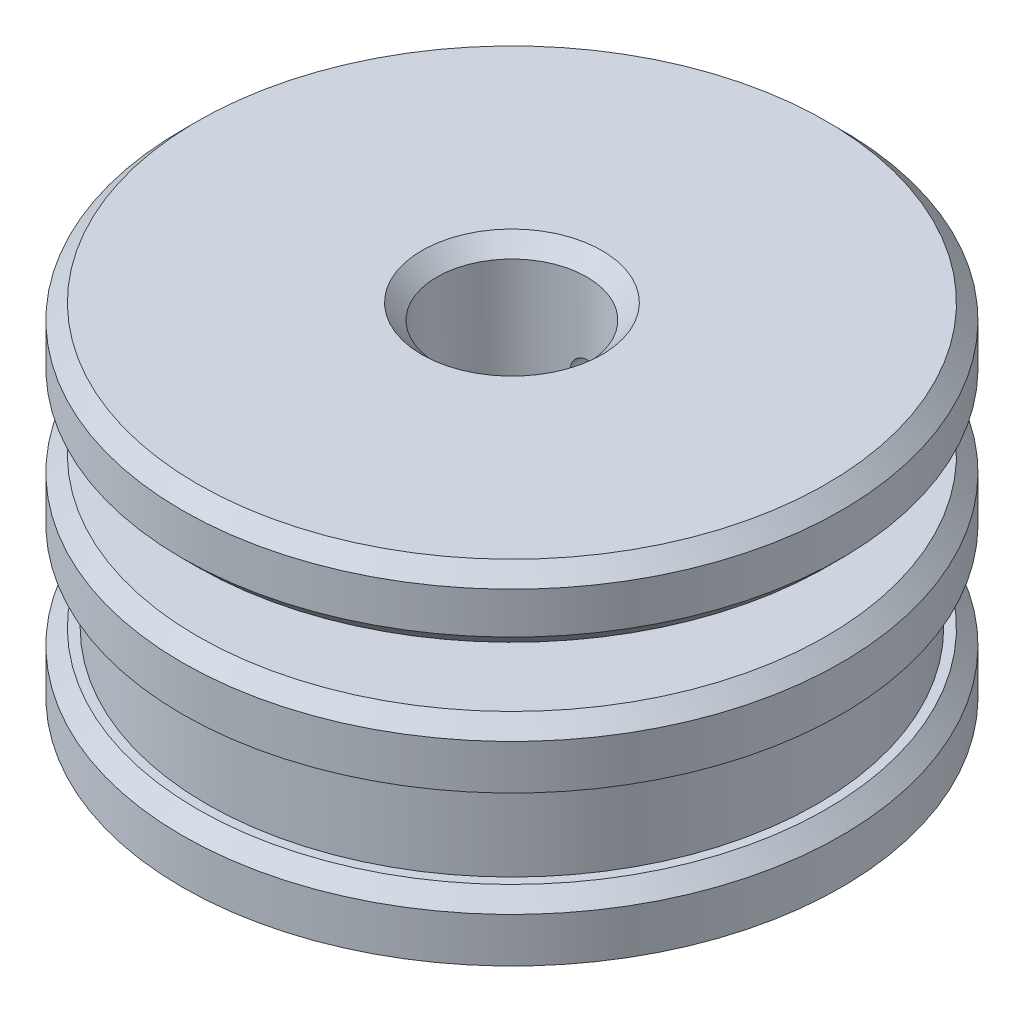
SolidWorks part; units mm, degrees
ref_plane "Front Plane" through (0, 0, 0) normal (0, 0, 1) x (1, 0, 0)
ref_plane "Top Plane" through (0, 0, 0) normal (0, 1, 0) x (1, 0, 0)
ref_plane "Right Plane" through (0, 0, 0) normal (1, 0, 0) x (0, 0, -1)
sketch "Sketch1" plane through (0, 0, 0) normal (0, 1, 0) x (1, 0, 0)
  circle A0 centre (0, 0) radius 2.3813
  circle A1 centre (0, 0) radius 11
  dimension "D1" = 4.7625
  dimension "D2" = 22
extrude "Boss-Extrude1" add sketch "Sketch1" along normal blind 2
sketch "Sketch2" plane through (0, 2, 0) normal (0, 1, 0) x (1, 0, 0)
  circle A0 centre (0, 0) radius 1.1375
  circle A1 centre (0, 0) radius 10.19
  dimension "D1" = 2.275
  dimension "D2" = 20.38
extrude "Boss-Extrude2" add sketch "Sketch2" along normal blind 1.5
sketch "Sketch3" plane through (0, 3.5, 0) normal (0, 1, 0) x (1, 0, 0)
  circle A0 centre (0, 0) radius 10.19
  circle A1 centre (0, 0) radius 2.5
  circle A2 centre (0, 0) radius 10.19 construction
  dimension "D1" = 5
extrude "Boss-Extrude3" add sketch "Sketch3" along normal blind 1.5
sketch "Sketch5" plane through (0, 5, 0) normal (0, 1, 0) x (1, 0, 0)
  circle A0 centre (0, 0) radius 2.5
  circle A1 centre (0, 0) radius 11
  circle A2 centre (0, 0) radius 11 construction
  circle A3 centre (0, 0) radius 2.5 construction
extrude "Boss-Extrude4" add sketch "Sketch5" along normal blind 2
sketch "Sketch6" plane through (0, 7, 0) normal (0, 1, 0) x (1, 0, 0)
  circle A0 centre (0, 0) radius 2.5
  circle A1 centre (0, 0) radius 6.4
  circle A2 centre (0, 0) radius 2.5 construction
  dimension "D1" = 12.8
extrude "Boss-Extrude5" add sketch "Sketch6" along normal blind 2
sketch "Sketch7" plane through (0, 9, 0) normal (0, 1, 0) x (1, 0, 0)
  circle A0 centre (0, 0) radius 2.5
  circle A1 centre (0, 0) radius 11
  circle A2 centre (0, 0) radius 11 construction
  circle A3 centre (0, 0) radius 2.5 construction
extrude "Boss-Extrude6" add sketch "Sketch7" along normal blind 2.4
sketch "Sketch8" plane through (0, 0, 0) normal (0, 0, 1) x (1, 0, 0)
  line L0 (0, 0) -> (0, 2) construction
  line L1 (0, 2) -> (0, 5) construction
  line L2 (0, 5) -> (0, 7) construction
  line L3 (0, 7) -> (0, 9) construction
  line L4 (10.19, 2) -> (-10.19, 2) construction
  line L5 (-10.19, 5) -> (10.19, 5) construction
  line L6 (6.4, 7) -> (-6.4, 7) construction
  line L7 (-6.4, 9) -> (6.4, 9) construction
  circle A0 centre (0, 8) radius 0.5
  circle A1 centre (0, 4) radius 0.5
  dimension "D1" = 1
  dimension "D2" = 1
  dimension "D4" = 2
  dimension "D3" = 1
extrude "Cut-Extrude1" cut sketch "Sketch8" against normal through all
chamfer "Chamfer1" distance 0.508 angle 45 5 edges at (0, 11.4, 11) (0, 11.4, 2.5) (0, 2, 11) (0, 7, 11) (0, 9, 11)
